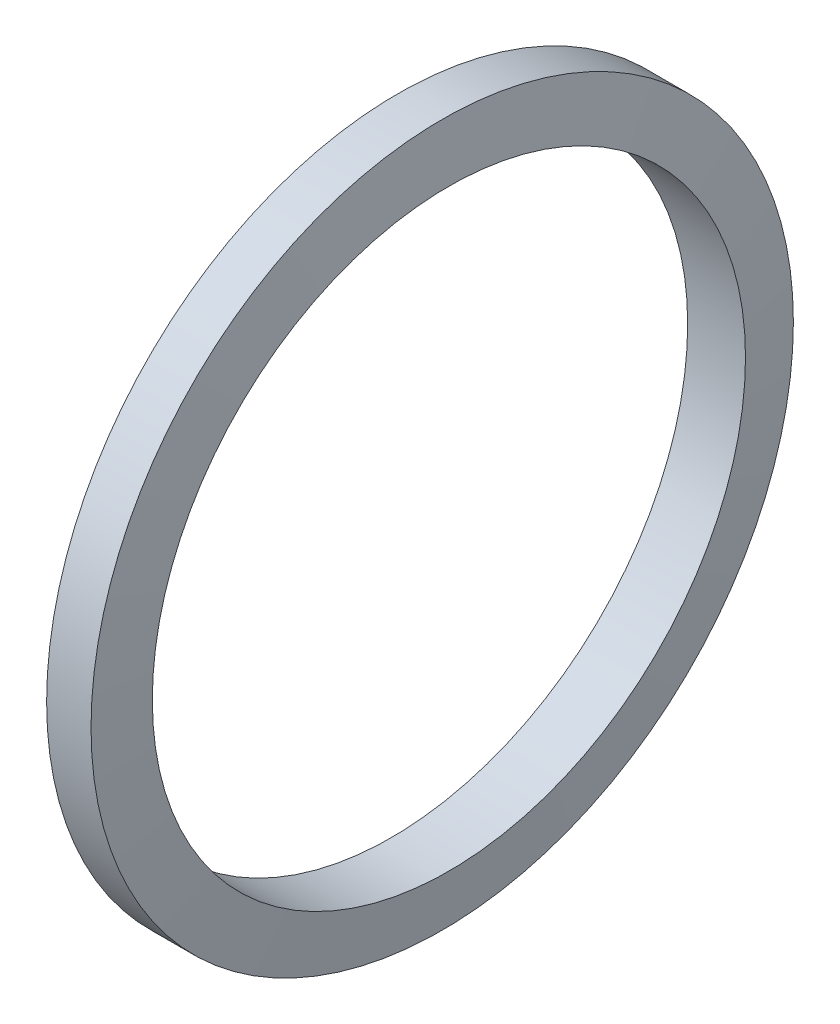
SolidWorks part; units mm, degrees
ref_plane "前视基准面" through (0, 0, 0) normal (0, 0, 1) x (1, 0, 0)
ref_plane "上视基准面" through (0, 0, 0) normal (0, 1, 0) x (1, 0, 0)
ref_plane "右视基准面" through (0, 0, 0) normal (1, 0, 0) x (0, 0, -1)
sketch "尺寸草图" plane through (0, 0, 0) normal (0, 0, 1) x (1, 0, 0)
  line L0 (-7.8111, 80.15) -> (-6, 94.9)
  line L1 (-6, 94.9) -> (6, 94.9)
  line L2 (6, 94.9) -> (7.8111, 80.15)
  line L3 (-7.8111, 80.15) -> (7.8111, 80.15)
  line L4 (-2.6163, 0) -> (3.6413, 0) construction
  line L5 (0, 94.9) -> (0, -9.1167) construction
  dimension "d1" = 160.3
  dimension "D2" = 7
  dimension "D" = 189.8
  dimension "D3" = 7
  dimension "B" = 12
revolve "旋转1" add sketch "尺寸草图" angle 360 about L4
